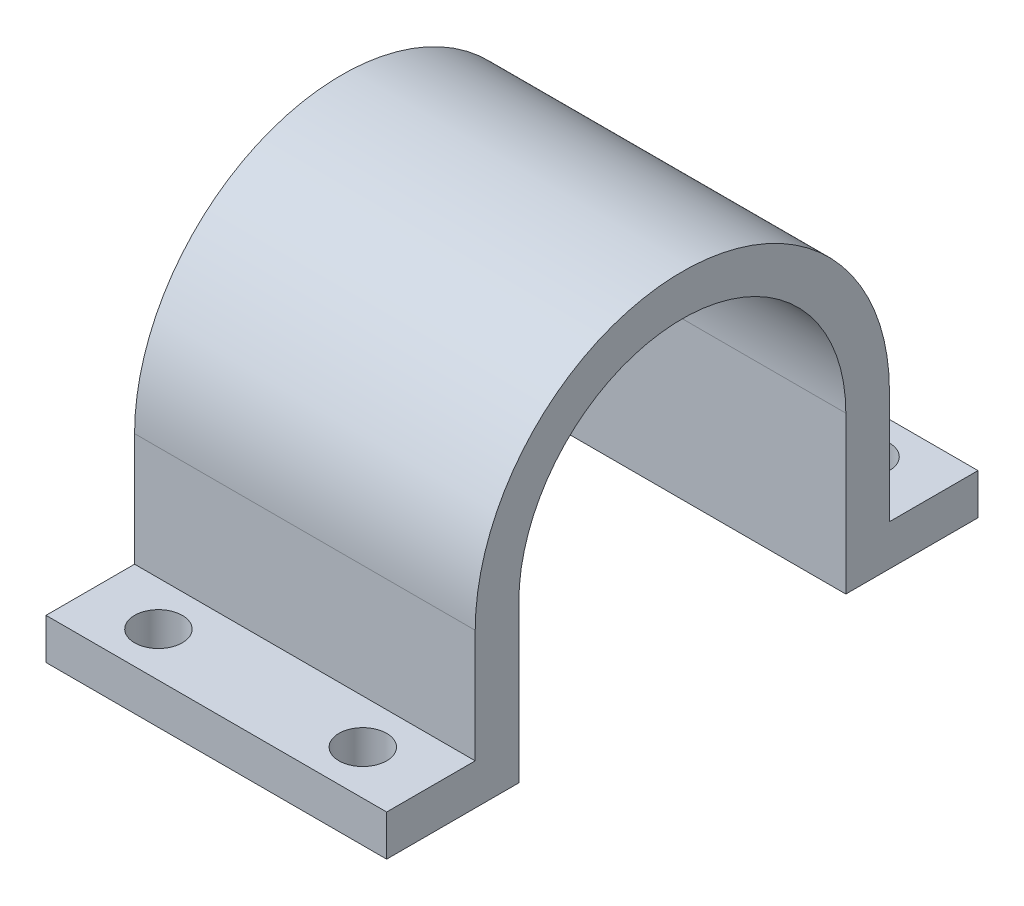
SolidWorks part; units mm, degrees
ref_plane "Front Plane" through (0, 0, 0) normal (0, 0, 1) x (1, 0, 0)
ref_plane "Top Plane" through (0, 0, 0) normal (0, 1, 0) x (1, 0, 0)
ref_plane "Right Plane" through (0, 0, 0) normal (1, 0, 0) x (0, 0, -1)
sketch "Sketch1" plane through (0, 0, 0) normal (1, 0, 0) x (0, 0, -1)
  line L0 (-21.7, 0) -> (-21.7, 3)
  line L1 (55, 0) -> (-55, 0) construction
  line L3 (-21.7, 3) -> (21.7, 3) construction
  line L5 (21.7, 3) -> (21.7, 0)
  line L6 (21.7, 0) -> (-21.7, 0)
  line L7 (0, 55) -> (0, -55) construction
  line L8 (0, 26.5) -> (0, 0) construction
  line L9 (-15.2, 11.3) -> (-15.2, 3)
  line L13 (-21.7, 3) -> (-15.2, 3)
  line L15 (15.2, 11.3) -> (15.2, 3)
  line L16 (15.2, 3) -> (21.7, 3)
  arc A1 (-15.2, 11.3) -> (15.2, 11.3) centre (0, 11.3) cw
  dimension "D3" = 15.2
  dimension "D4" = 21.7
  dimension "D1" = 43.4
  dimension "D2" = 3
  dimension "D5" = 26.5
extrude "Boss-Extrude1" add sketch "Sketch1" along normal blind 25
sketch "Sketch2" plane through (25, 0, 0) normal (1, 0, 0) x (0, 0, -1)
  line L0 (-12, 11.5) -> (-12, 0)
  line L1 (13.75, 0) -> (-13.75, 0) construction
  line L2 (12, 11.5) -> (12, 0)
  line L5 (-12, 0) -> (12, 0)
  line L6 (0, 13.75) -> (0, -13.75) construction
  line L7 (0, 23.5) -> (0, 0) construction
  arc A2 (-12, 11.5) -> (12, 11.5) centre (0, 11.5) cw
  dimension "D1" = 23.5
  dimension "D3" = 12
extrude "Cut-Extrude1" cut sketch "Sketch2" against normal through all
sketch "Sketch3" plane through (0, 3, 0) normal (0, 1, 0) x (1, 0, 0)
  line L0 (25, 21.7) -> (25, 15.2) construction
  line L1 (25, 21.7) -> (0, 21.7) construction
  line L2 (25, -21.7) -> (0, -21.7) construction
  circle A0 centre (5, -18.45) radius 1.75
  circle A1 centre (20, -18.45) radius 1.75
  circle A2 centre (5, 18.45) radius 1.75
  circle A3 centre (20, 18.45) radius 1.75
  dimension "D1" = 3.5
  dimension "D2" = 15
  dimension "D3" = 5
  dimension "D4" = 3.25
  dimension "D5" = 3.25
extrude "Cut-Extrude2" cut sketch "Sketch3" against normal through all
